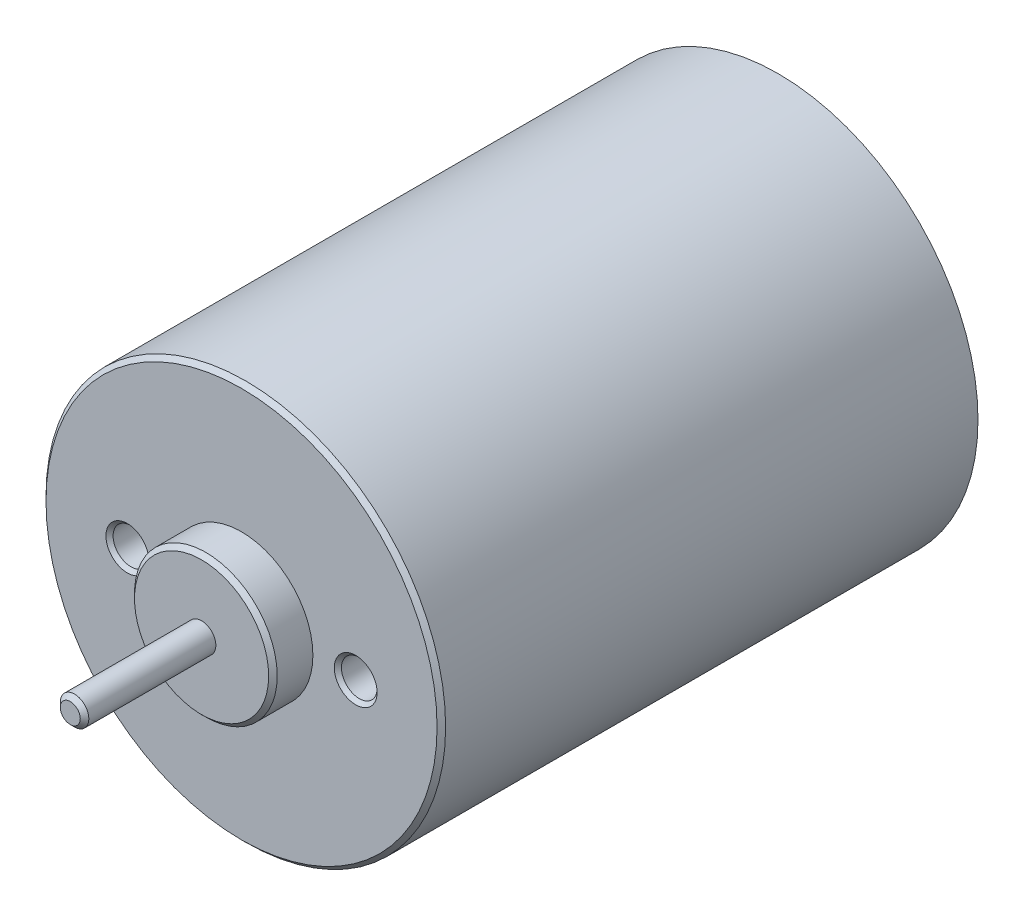
SolidWorks part; units mm, degrees
ref_plane "Front Plane" through (0, 0, 0) normal (0, 0, 1) x (1, 0, 0)
ref_plane "Top Plane" through (0, 0, 0) normal (0, 1, 0) x (1, 0, 0)
ref_plane "Right Plane" through (0, 0, 0) normal (1, 0, 0) x (0, 0, -1)
sketch "Sketch1" plane through (0, 0, 0) normal (0, 0, 1) x (1, 0, 0)
  circle A0 centre (0, 0) radius 14
  dimension "D1" = 28
extrude "Boss-Extrude1" add sketch "Sketch1" along normal blind 37.6
sketch "Sketch2" plane through (0, 0, 37.6) normal (0, 0, 1) x (1, 0, 0)
  circle A0 centre (0, 0) radius 5
  dimension "D1" = 10
extrude "Boss-Extrude2" add sketch "Sketch2" along normal blind 2.8
sketch "Sketch3" plane through (0, 0, 40.4) normal (0, 0, 1) x (1, 0, 0)
  circle A0 centre (0, 0) radius 1
  dimension "D1" = 2
extrude "Boss-Extrude3" add sketch "Sketch3" along normal blind 9.2
sketch "Sketch4" plane through (0, 0, 0) normal (0, 0, -1) x (-1, 0, 0)
  circle A0 centre (0, 0) radius 5
  dimension "D1" = 10
extrude "Boss-Extrude4" add sketch "Sketch4" along normal blind 2.6
sketch "Sketch5" plane through (0, 0, -2.6) normal (0, 0, -1) x (-1, 0, 0)
  circle A0 centre (0, 0) radius 1
extrude "Boss-Extrude5" add sketch "Sketch5" along normal blind 1.4
chamfer "Chamfer1" distance 0.3 angle 45 3 edges at (-5, 0, -2.6) (5, 0, 40.4) (14, 0, 37.6)
chamfer "Chamfer2" distance 0.3 angle 45 2 edges at (-1, 0, -4) (1, 0, 49.6)
sketch "Sketch6" plane through (0, 0, 37.6) normal (0, 0, 1) x (1, 0, 0)
  line L0 (15.4, 0) -> (-15.4, 0) construction
  line L1 (0, -15.4) -> (0, 15.4) construction
  circle A0 centre (-8, 0) radius 1.25
  circle A1 centre (8, 0) radius 1.25
  dimension "D1" = 8
  dimension "D2" = 8
extrude "Cut-Extrude1" cut sketch "Sketch6" against normal blind 2.5
chamfer "Chamfer3" distance 0.25 angle 45 2 edges at (9.25, 0, 37.6) (-6.75, 0, 37.6)
